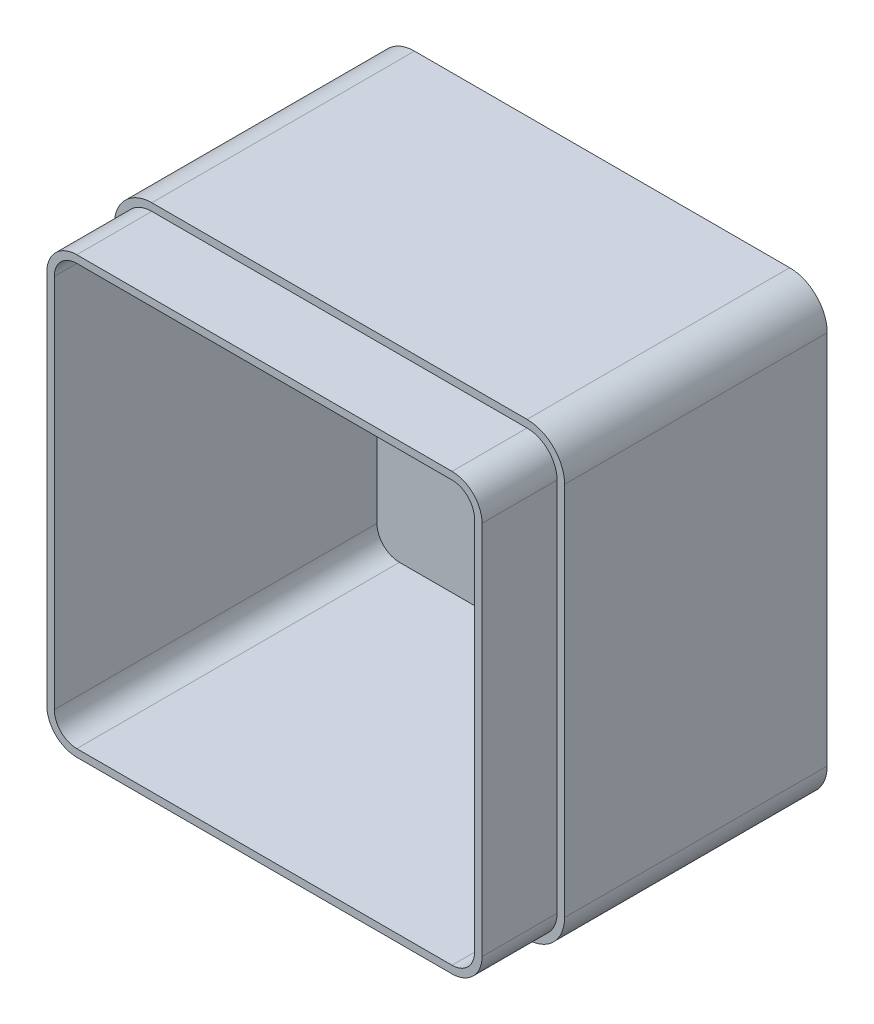
SolidWorks part; units mm, degrees
ref_plane "Front Plane" through (0, 0, 0) normal (0, 0, 1) x (1, 0, 0)
ref_plane "Top Plane" through (0, 0, 0) normal (0, 1, 0) x (1, 0, 0)
ref_plane "Right Plane" through (0, 0, 0) normal (1, 0, 0) x (0, 0, -1)
sketch "Sketch1" plane through (0, 0, 0) normal (0, 0, 1) x (1, 0, 0)
  line L1 (-120, 120) -> (0, 120)
  line L2 (-120, 120) -> (-120, 0)
  line L3 (-120, 0) -> (0, 0)
  line L4 (0, 120) -> (0, 0)
  dimension "D1" = 120
  dimension "D2" = 120
extrude "Boss-Extrude1" add sketch "Sketch1" along normal blind 90
fillet "Fillet1" radius 10 4 edges at (-120, 0, 45) (-120, 120, 45) (0, 120, 45) (0, 0, 45)
shell "Shell1" thickness 4
sketch "Sketch9" plane through (0, 0, 90) normal (0, 0, 1) x (1, 0, 0)
  line L0 (-118, 110) -> (-118, 10)
  line L1 (-110, 2) -> (-10, 2)
  line L2 (-2, 10) -> (-2, 110)
  line L3 (-10, 118) -> (-110, 118)
  line L4 (-120, 110) -> (-120, 10)
  line L5 (-110, 0) -> (-10, 0)
  line L6 (0, 10) -> (0, 110)
  line L7 (-10, 120) -> (-110, 120)
  line L8 (-120, 110) -> (-120, 10)
  line L9 (-110, 0) -> (-10, 0)
  line L10 (0, 10) -> (0, 110)
  line L11 (-10, 120) -> (-110, 120)
  arc A0 (-118, 10) -> (-110, 2) centre (-110, 10) ccw
  arc A1 (-10, 2) -> (-2, 10) centre (-10, 10) ccw
  arc A2 (-2, 110) -> (-10, 118) centre (-10, 110) ccw
  arc A3 (-110, 118) -> (-118, 110) centre (-110, 110) ccw
  arc A4 (-120, 10) -> (-110, 0) centre (-110, 10) ccw
  arc A5 (-10, 0) -> (0, 10) centre (-10, 10) ccw
  arc A6 (0, 110) -> (-10, 120) centre (-10, 110) ccw
  arc A7 (-110, 120) -> (-120, 110) centre (-110, 110) ccw
  arc A8 (-120, 10) -> (-110, 0) centre (-110, 10) ccw
  arc A9 (-10, 0) -> (0, 10) centre (-10, 10) ccw
  arc A10 (0, 110) -> (-10, 120) centre (-10, 110) ccw
  arc A11 (-110, 120) -> (-120, 110) centre (-110, 110) ccw
  dimension "D1" = 0
  dimension "D2" = 2
extrude "Cut-Extrude3" cut sketch "Sketch9" against normal blind 20
